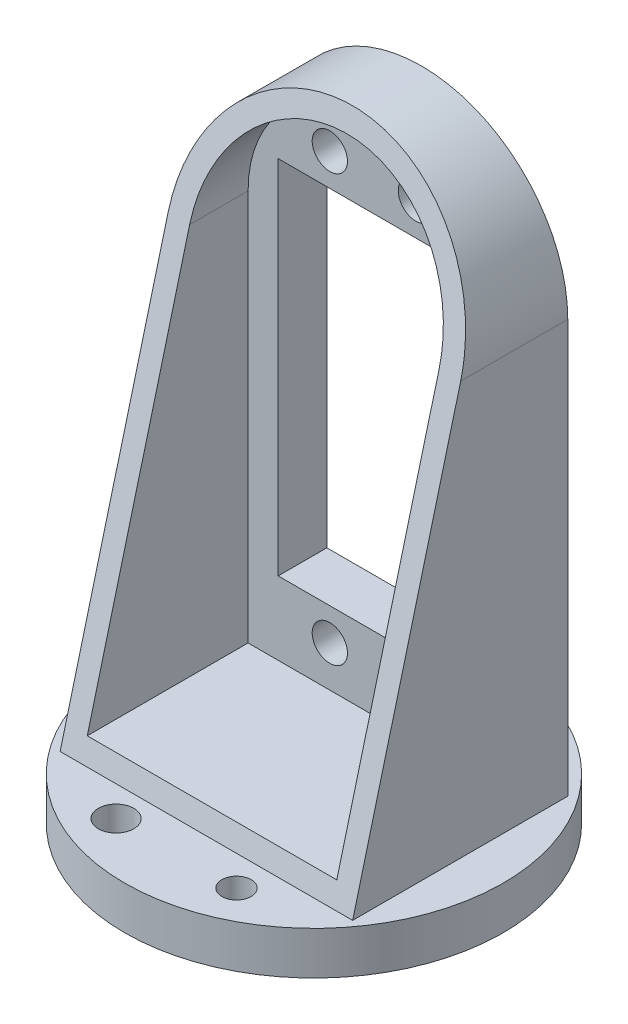
SolidWorks part; units mm, degrees
ref_plane "Alzado" through (0, 0, 0) normal (0, 0, 1) x (1, 0, 0)
ref_plane "Planta" through (0, 0, 0) normal (0, 1, 0) x (1, 0, 0)
ref_plane "Vista lateral" through (0, 0, 0) normal (1, 0, 0) x (0, 0, -1)
sketch "Croquis1" plane through (0, 0, 0) normal (0, 1, 0) x (1, 0, 0)
  circle A0 centre (0, 0) radius 22
  dimension "D1" = 44
extrude "Saliente-Extruir1" add sketch "Croquis1" along normal blind 5
sketch "Croquis2" plane through (0, 5, 0) normal (0, 1, 0) x (1, 0, 0)
  line L0 (0, 22) -> (0, 17.5) construction
  line L1 (-7, -15.9997) -> (7, -15.9997) construction
  line L2 (0, 0) -> (-7, -15.9997) construction
  line L3 (0, 0) -> (7, -15.9997) construction
  circle A0 centre (0, 0) radius 22 construction
  circle A1 centre (0, 17.5) radius 2.05
  circle A2 centre (-7, -15.9997) radius 2.0651
  circle A3 centre (7, -15.9997) radius 1.702
  dimension "D2" = 4.1
  dimension "D1" = 4.5
  dimension "D3" = 14
  dimension "D4" = 17.464
  dimension "D5" = 17.464
extrude "Cortar-Extruir1" cut sketch "Croquis2" against normal blind 5
sketch "Croquis3" plane through (0, 5, 0) normal (0, 1, 0) x (1, 0, 0)
  line L0 (-22, 0) -> (-17, 0) construction
  line L1 (22, 0) -> (17, 0) construction
  line L2 (17, -12.5) -> (17, 12.5)
  line L3 (-17, -12.5) -> (-17, 12.5)
  line L4 (-17, 12.5) -> (17, 12.5)
  line L5 (17, -12.5) -> (-17, -12.5)
  circle A0 centre (0, 0) radius 22 construction
  point P11 (17, 0)
  point P14 (-17, 0)
  dimension "D1" = 5
  dimension "D2" = 5
  dimension "D3" = 25
  dimension "D4" = 25
extrude "Saliente-Extruir2" add sketch "Croquis3" along normal blind 48
sketch "Croquis4" plane through (0, 0, -12.5) normal (0, 0, -1) x (-1, 0, 0)
  line L0 (-17, 53) -> (17, 53) construction
  line L1 (-17, 53) -> (17, 53)
  arc A0 (17, 53) -> (-17, 53) centre (0, 53) ccw
extrude "Saliente-Extruir3" add sketch "Croquis4" against normal blind 25
sketch "Croquis5" plane through (0, 0, 12.5) normal (0, 0, 1) x (1, 0, 0)
  line L0 (0, 5) -> (0, 7.5)
  line L1 (-17, 5) -> (17, 5) construction
  line L2 (-14.5, 7.5) -> (14.5, 7.5)
  line L3 (17, 53) -> (17, 5) construction
  line L5 (-14.5, 7.5) -> (-14.5, 53)
  line L7 (14.5, 7.5) -> (14.5, 53)
  arc A0 (14.5, 53) -> (-14.5, 53) centre (0, 53) ccw
  point P8 (0, 7.5)
  dimension "D1" = 2.5
  dimension "D2" = 2.5
extrude "Cortar-Extruir2" cut sketch "Croquis5" against normal blind 19.346 contours L7 A0 L5 L2
sketch "Croquis6" plane through (0, 0, -6.846) normal (0, 0, 1) x (1, 0, 0)
  line L0 (-5, 12.2506) -> (0, 7.5) construction
  line L2 (-11, 16) -> (11, 16)
  line L3 (11, 16) -> (11, 58)
  line L4 (11, 58) -> (-11, 58)
  line L5 (-11, 58) -> (-11, 16)
  line L6 (-14.5, 7.5) -> (14.5, 7.5) construction
  line L7 (0, 7.5) -> (5, 12.2506) construction
  line L8 (-5, 12.2506) -> (5, 12.2506) construction
  line L9 (-5, 14.3) -> (-5, 16) construction
  line L10 (5, 14.3) -> (5, 16) construction
  line L11 (0, 58) -> (-5, 61.75) construction
  line L12 (-5, 61.75) -> (5, 61.75) construction
  line L13 (5, 61.75) -> (0, 58) construction
  line L14 (5, 59.7) -> (5, 58) construction
  circle A0 centre (-5, 12.2506) radius 2.0494
  circle A1 centre (5, 12.2506) radius 2.0494
  circle A2 centre (-5, 61.75) radius 2.05
  circle A3 centre (5, 61.75) radius 2.05
  point P8 (0, 16)
  dimension "D7" = 1.7
  dimension "D1" = 6.897
  dimension "D2" = 22
  dimension "D3" = 42
  dimension "D4" = 6.897
  dimension "D5" = 10
  dimension "D6" = 1.7
  dimension "D8" = 10
  dimension "D9" = 6.25
  dimension "D10" = 6.25
  dimension "D11" = 1.7
extrude "Cortar-Extruir3" cut sketch "Croquis6" against normal blind 19.346
sketch "Croquis7" plane through (17, 0, 0) normal (1, 0, 0) x (0, 0, -1)
  line L0 (-12.5, 5) -> (12.5, 5)
  line L1 (-12.5, 5) -> (10.4005, 92.5592)
  line L2 (10.4005, 92.5592) -> (-12.5, 92.5592)
  line L3 (-12.5, 92.5592) -> (-12.5, 5)
  line M5 (12.5, 53) -> (-12.5, 53)
  line M6 (-12.5, 53) -> (-12.5, 5)
  dimension "D1" = 75.343
extrude "Cortar-Extruir4" cut sketch "Croquis7" against normal blind 49.346 contours L2 L3 L1 M5 | L1 M6 M5
